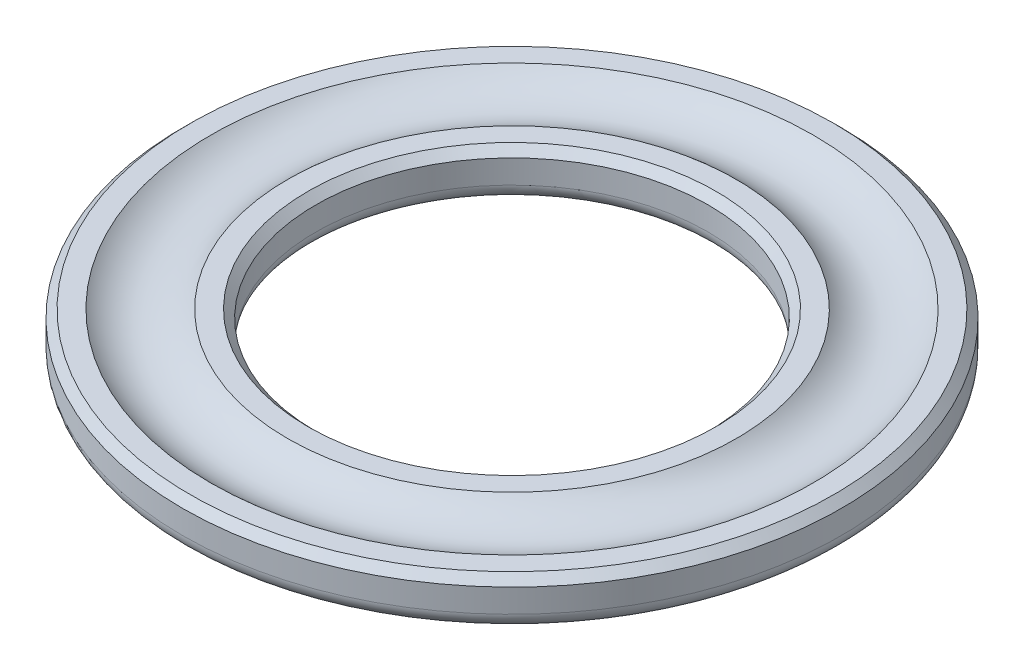
SolidWorks part; units mm, degrees
material "ABS"
ref_plane "Front Plane" through (0, 0, 0) normal (0, 0, 1) x (1, 0, 0)
ref_plane "Top Plane" through (0, 0, 0) normal (0, 1, 0) x (1, 0, 0)
ref_plane "Right Plane" through (0, 0, 0) normal (1, 0, 0) x (0, 0, -1)
sketch "Sketch1" plane through (0, 0, 0) normal (0, 0, 1) x (1, 0, 0)
  line L0 (12.5, -2.5) -> (14.3005, -2.5)
  line L1 (21, -2.5) -> (21, -5.5)
  line L2 (21, -5.5) -> (12.5, -5.5)
  line L3 (12.5, -5.5) -> (12.5, -2.5)
  line L4 (16.75, -5.5) -> (16.75, -2.5) construction
  line L5 (16.75, 5.5) -> (16.75, 2.5) construction
  line L6 (12.5, 2.5) -> (21, 2.5) construction
  line L7 (12.5, 2.5) -> (12.5, 5.5) construction
  line L8 (12.5, 5.5) -> (21, 5.5) construction
  line L9 (21, 2.5) -> (21, 5.5) construction
  line L10 (0, 0) -> (21, 0) construction
  line L11 (19.1995, -2.5) -> (21, -2.5)
  line L12 (14.3005, -2.5) -> (19.1995, -2.5) construction
  line L13 (0, 5.5) -> (0, -5.5) construction
  circle A0 centre (16.75, 0) radius 3 construction
  arc A1 (14.3005, -2.5) -> (19.1995, -2.5) centre (16.75, 0) ccw
  dimension "D1" = 6
  dimension "D6" = 3.5
  dimension "D2" = 12.5
  dimension "D3" = 21
  dimension "D4" = 3
  dimension "D7" = 5
revolve "Revolve1" add sketch "Sketch1" angle 360 about L13
chamfer "Chamfer1" distance 0.5 angle 45 2 edges at (0, -2.5, 12.5) (0, -2.5, 21)
fillet "Fillet2" radius 1 2 edges at (0, -5.5, 12.5) (0, -5.5, 21)
